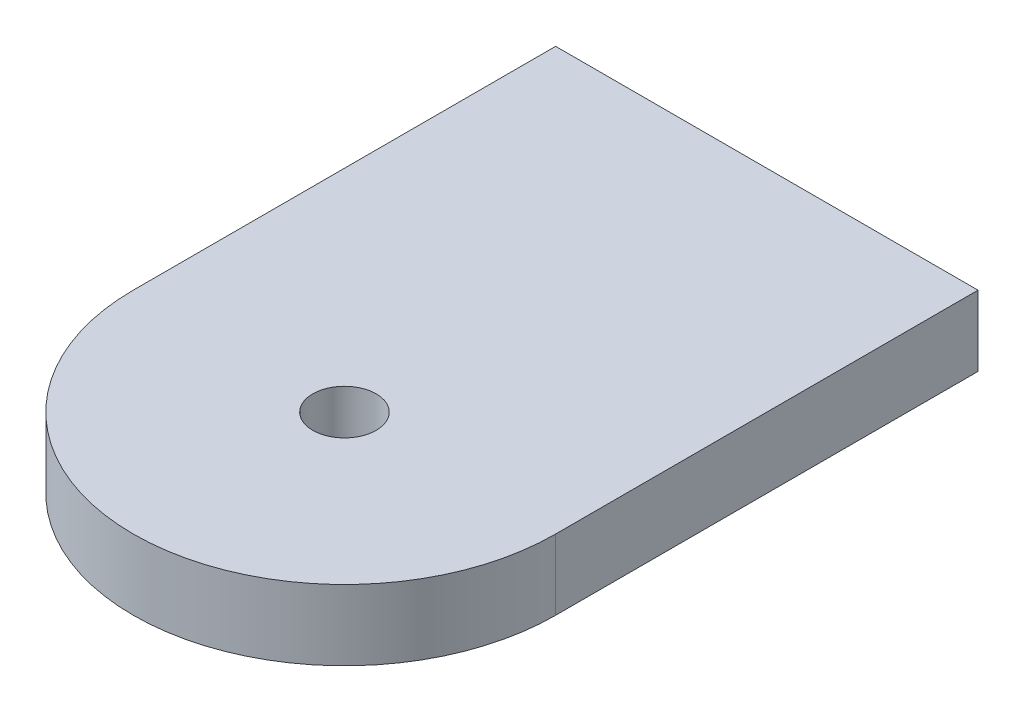
SolidWorks part; units mm, degrees
ref_plane "Front Plane" through (0, 0, 0) normal (0, 0, 1) x (1, 0, 0)
ref_plane "Top Plane" through (0, 0, 0) normal (0, 1, 0) x (1, 0, 0)
ref_plane "Right Plane" through (0, 0, 0) normal (1, 0, 0) x (0, 0, -1)
sketch "Sketch1" plane through (0, 0, 0) normal (0, 1, 0) x (1, 0, 0)
  line L0 (0, 0) -> (6, 0)
  line L1 (6, 0) -> (6, -6)
  line L2 (0, 0) -> (0, -6)
  arc A0 (0, -6) -> (6, -6) centre (3, -6) ccw
  circle A1 centre (3, -6) radius 0.45
  dimension "D3" = 0.9
  dimension "D1" = 6
  dimension "D2" = 6
extrude "Boss-Extrude1" add sketch "Sketch1" along normal blind 1 contours A0 L1 L0 L2 | A1
equation "\"width\"= 6mm"
equation "\"D1@Sketch1\"=\"width\""
equation "\"D2@Sketch1\"=\"width\""
equation "\"pinDia\"= 0.9mm"
equation "\"D3@Sketch1\"=\"pinDia\""
